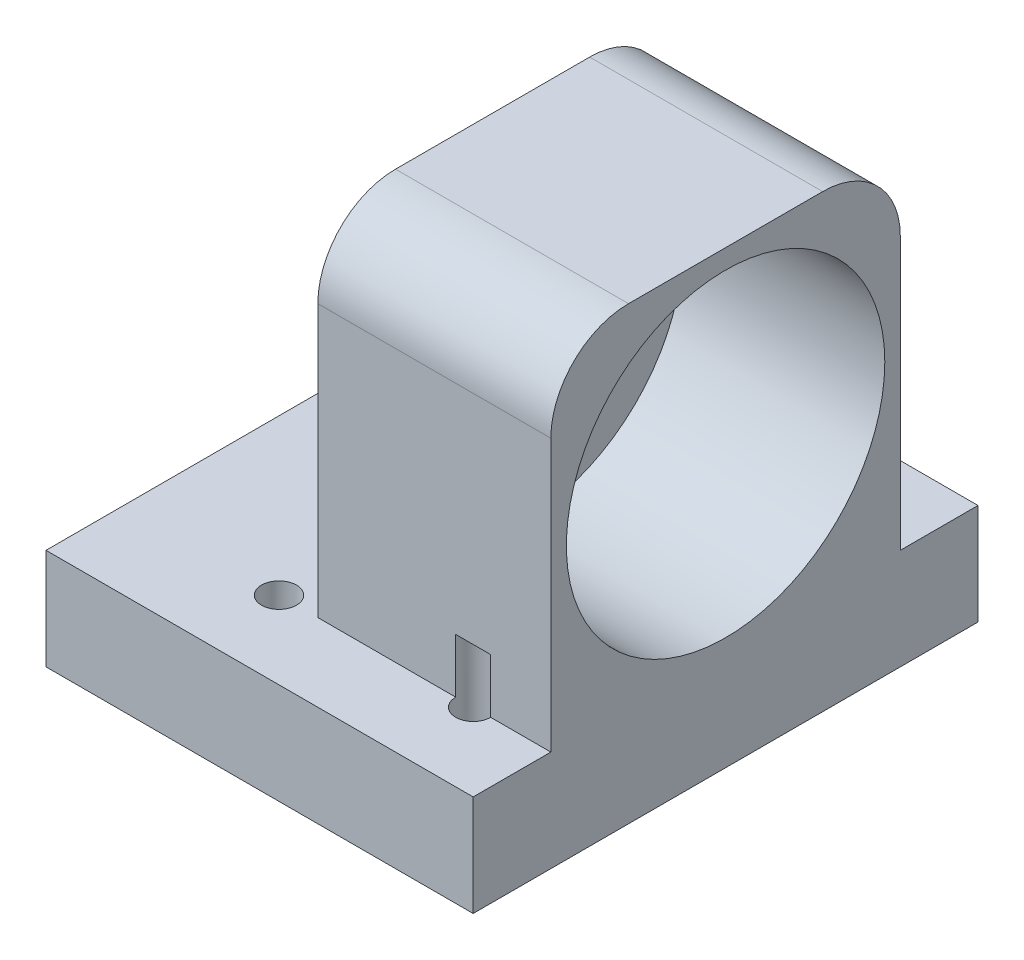
SolidWorks part; units mm, degrees
ref_plane "Front Plane" through (0, 0, 0) normal (0, 0, 1) x (1, 0, 0)
ref_plane "Top Plane" through (0, 0, 0) normal (0, 1, 0) x (1, 0, 0)
ref_plane "Right Plane" through (0, 0, 0) normal (1, 0, 0) x (0, 0, -1)
sketch "Sketch1" plane through (0, 0, 0) normal (0, 1, 0) x (1, 0, 0)
  line L1 (-32.5, 32.5) -> (22.5, 32.5)
  line L2 (-32.5, 32.5) -> (-32.5, -32.5)
  line L3 (-32.5, -32.5) -> (22.5, -32.5)
  line L4 (22.5, 32.5) -> (22.5, -32.5)
  dimension "D1" = 55
  dimension "D2" = 65
  dimension "D3" = 32.5
  dimension "D4" = 22.5
extrude "Boss-Extrude1" add sketch "Sketch1" along normal blind 13
sketch "Sketch2" plane through (0, 13, 0) normal (0, 1, 0) x (1, 0, 0)
  line L0 (22.5, -32.5) -> (22.5, 32.5) construction
  line L1 (22.5, 22.5) -> (-7.5, 22.5)
  line L2 (22.5, 22.5) -> (22.5, -22.5)
  line L3 (22.5, -22.5) -> (-7.5, -22.5)
  line L4 (-7.5, 22.5) -> (-7.5, -22.5)
  dimension "D1" = 45
  dimension "D2" = 22.5
  dimension "D3" = 30
extrude "Boss-Extrude2" add sketch "Sketch2" along normal blind 50
sketch "Sketch5" plane through (22.5, 0, 0) normal (1, 0, 0) x (0, 0, -1)
  circle A0 centre (0, 35) radius 20.5
  dimension "D1" = 41
  dimension "D2" = 35
extrude "Cut-Extrude1" cut sketch "Sketch5" against normal blind 26
sketch "Sketch7" plane through (-3.5, 0, 0) normal (1, 0, 0) x (0, 0, -1)
  circle A0 centre (0, 35) radius 7
  dimension "D1" = 14
  dimension "D2" = 35
extrude "Cut-Extrude2" cut sketch "Sketch7" against normal blind 20
sketch "Sketch8" plane through (0, 0, 0) normal (0, -1, 0) x (-1, 0, 0)
  line L0 (32.5, 32.5) -> (32.5, -32.5) construction
  circle A0 centre (12.5, -22.5) radius 2.25
  circle A1 centre (12.5, 22.5) radius 2.25
  circle A2 centre (-12.5, 22.5) radius 2.25
  circle A3 centre (-12.5, -22.5) radius 2.25
  dimension "D1" = 4.5
  dimension "D2" = 4.5
  dimension "D3" = 4.5
  dimension "D4" = 4.5
  dimension "D5" = 25
  dimension "D6" = 22.5
  dimension "D7" = 22.5
  dimension "D8" = 22.5
  dimension "D9" = 22.5
  dimension "D10" = 20
  dimension "D11" = 20
  dimension "D12" = 25
extrude "Cut-Extrude3" cut sketch "Sketch8" against normal blind 20
fillet "Fillet1" radius 10 1 edges at (-32.5, 6.5, -32.5)
sketch "Sketch9" plane through (0, 63, 0) normal (0, 1, 0) x (1, 0, 0)
  line L1 (-7.5, 22.5) -> (22.5, 22.5)
  line L2 (-7.5, 22.5) -> (-7.5, -22.5)
  line L3 (-7.5, -22.5) -> (22.5, -22.5)
  line L4 (22.5, 22.5) -> (22.5, -22.5)
extrude "Cut-Extrude4" cut sketch "Sketch9" against normal blind 5
fillet "Fillet4" radius 10 1 edges at (7.5, 58, 22.5)
fillet "Fillet5" radius 10 1 edges at (7.5, 58, -22.5)
